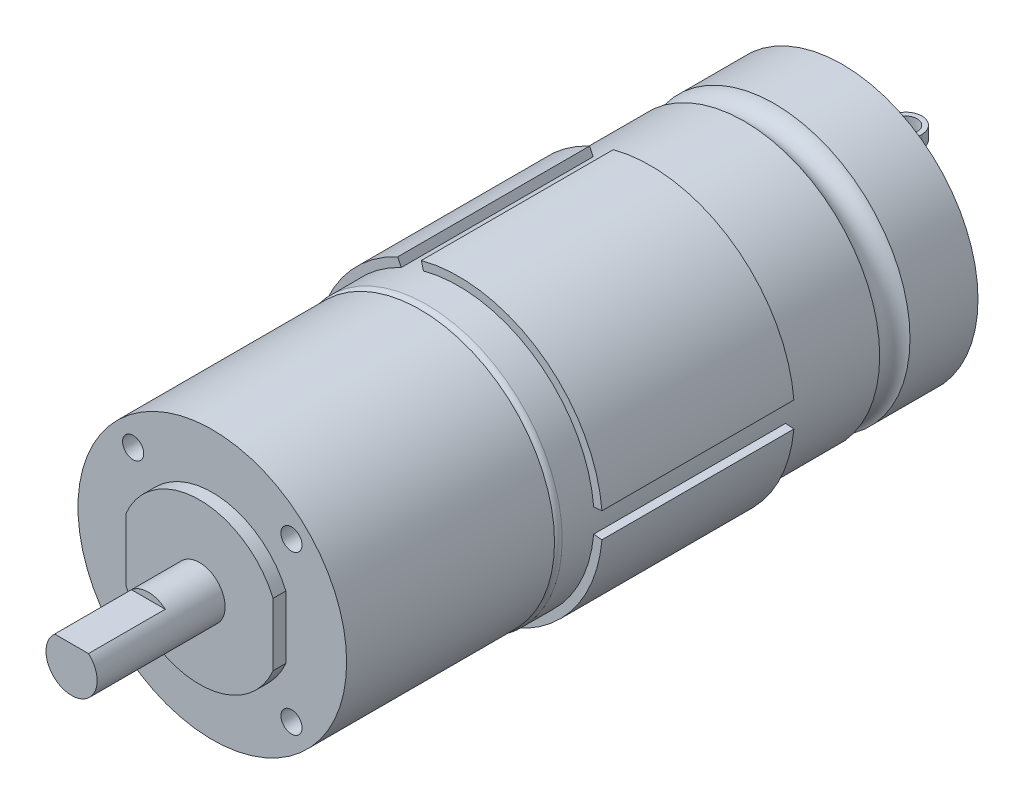
SolidWorks part; units mm, degrees
ref_plane "Piano frontale" through (0, 0, 0) normal (0, 0, 1) x (1, 0, 0)
ref_plane "Piano superiore" through (0, 0, 0) normal (0, 1, 0) x (1, 0, 0)
ref_plane "Piano destro" through (0, 0, 0) normal (1, 0, 0) x (0, 0, -1)
sketch "Schizzo1" plane through (0, 0, 0) normal (0, 0, 1) x (1, 0, 0)
  circle A0 centre (0, 0) radius 21.2
  dimension "D1" = 42.4
extrude "Estrusione-Estrusione1" add sketch "Schizzo1" along normal blind 66
sketch "Schizzo2" plane through (0, 0, 66) normal (0, 0, 1) x (1, 0, 0)
  circle A0 centre (0, 0) radius 21
  dimension "D1" = 42
extrude "Estrusione-Estrusione2" add sketch "Schizzo2" along normal blind 32.5 separate body
sketch "Schizzo3" plane through (0, 0, 98.5) normal (0, 0, 1) x (1, 0, 0)
  circle A0 centre (0, 0) radius 12.5
  dimension "D1" = 25
extrude "Estrusione-Estrusione3" add sketch "Schizzo3" along normal blind 2
sketch "Schizzo4" plane through (0, 0, 100.5) normal (0, 0, 1) x (1, 0, 0)
  line L0 (-12.5, 0) -> (12.5, 0) construction
  line L1 (0, 12.5) -> (0, -12.5) construction
  line L2 (-11.5, 4.899) -> (-11.5, -4.899)
  line L3 (11.5, 4.899) -> (11.5, -4.899)
  circle A1 centre (0, 0) radius 12.5 construction
  arc A4 (11.5, -4.899) -> (11.5, 4.899) centre (0, 0) ccw
  arc A5 (-11.5, 4.899) -> (-11.5, -4.899) centre (0, 0) ccw
  dimension "D1" = 23
  dimension "D2" = 11.5
extrude "Taglio-Estrusione5" cut sketch "Schizzo4" against normal blind 2
sketch "Schizzo5" plane through (0, 0, 100.5) normal (0, 0, 1) x (1, 0, 0)
  circle A0 centre (0, 0) radius 4
  dimension "D1" = 8
extrude "Estrusione-Estrusione4" add sketch "Schizzo5" along normal blind 20
sketch "Schizzo6" plane through (0, 0, 120.5) normal (0, 0, 1) x (1, 0, 0)
  line L0 (-4, 0) -> (4, 0) construction
  line L1 (-2.6458, 3) -> (2.6458, 3)
  circle A1 centre (0, 0) radius 4 construction
  arc A4 (2.6458, 3) -> (-2.6458, 3) centre (0, 0) ccw
  dimension "D1" = 3
extrude "Taglio-Estrusione6" cut sketch "Schizzo6" against normal blind 12
sketch "Schizzo7" plane through (0, 0, 98.5) normal (0, 0, 1) x (1, 0, 0)
  line L2 (0, 0) -> (21, 0) construction
  line L3 (0, 0) -> (14.8492, 14.8492) construction
  circle A1 centre (12.3744, 12.3744) radius 2
  circle A5 centre (0, 0) radius 17.5 construction
  circle A8 centre (12.3744, -12.3744) radius 2
  circle A9 centre (-12.3744, -12.3744) radius 2
  circle A10 centre (-12.3744, 12.3744) radius 2
  point P1 (0, 0)
  point P4 (13.6196, -14.5817)
  point P8 (0, 0)
  point P9 (0, 0)
  dimension "D1" = 4
  dimension "D4" = 35
  dimension "D2" = 45
  dimension "D3" = 4
sketch "Schizzo9" plane through (0, 0, 0) normal (1, 0, 0) x (0, 0, -1)
  line L0 (0, 21.2) -> (-66, 21.2) construction
  line L1 (0, -21.2) -> (0, 21.2) construction
  line L2 (-15.37, 21.2) -> (-10.63, 21.2)
  line L3 (0, 0) -> (-40.6364, 0) construction
  arc A0 (-15.37, 21.2) -> (-10.63, 21.2) centre (-13, 21.9957) ccw
  dimension "D1" = 2.5
  dimension "D2" = 10.63
  dimension "D3" = 4.74
revolve "Taglia-Rivoluzione1" cut sketch "Schizzo9" angle 360 about L3
sketch "Schizzo11" plane through (0, 0, 0) normal (0, 0, -1) x (-1, 0, 0)
  circle A0 centre (0, 0) radius 8.64
  dimension "D1" = 17.28
extrude "Estrusione-Estrusione5" add sketch "Schizzo11" along normal blind 5
sketch "Schizzo12" plane through (0, 0, -5) normal (0, 0, -1) x (-1, 0, 0)
  line L0 (-8.64, 0) -> (8.64, 0) construction
  line L1 (2.5, 6) -> (-2.5, 6)
  line L2 (2.5, 6) -> (2.5, 8)
  line L3 (2.5, 8) -> (-2.5, 8)
  line L4 (-2.5, 6) -> (-2.5, 8)
  line L5 (2.5, 6) -> (-2.5, 8) construction
  line L6 (2.5, 8) -> (-2.5, 6) construction
  line L7 (2.5, -8) -> (-2.5, -8)
  line L8 (2.5, -8) -> (2.5, -6)
  line L9 (2.5, -6) -> (-2.5, -6)
  line L10 (-2.5, -8) -> (-2.5, -6)
  line L11 (2.5, -8) -> (-2.5, -6) construction
  line L12 (2.5, -6) -> (-2.5, -8) construction
  line L13 (0, 8.64) -> (0, -8.64) construction
  circle A0 centre (0, 0) radius 8.64 construction
  circle A1 centre (0, 0) radius 8.64 construction
  point P0 (0, 7)
  point P5 (0, -7)
  point P19 (0, 0)
  point P20 (0, 0)
  dimension "D1" = 5
  dimension "D2" = 5
  dimension "D3" = 2
  dimension "D4" = 2
  dimension "D5" = 8
  dimension "D6" = 8
extrude "Estrusione-Estrusione6" add sketch "Schizzo12" along normal blind 7.42
sketch "Schizzo13" plane through (0, 8, 0) normal (0, 1, 0) x (1, 0, 0)
  line L0 (0, 0) -> (0, 12.42) construction
  line L1 (-2.5, 12.42) -> (2.5, 12.42) construction
  line L2 (-2.5, 5) -> (2.5, 5) construction
  line L3 (-2.5, 12.42) -> (-2.5, 5) construction
  line L4 (2.5, 12.42) -> (2.5, 5) construction
  line L5 (-2.5, 9.92) -> (2.5, 9.92) construction
  line L6 (-2.5, 9.92) -> (-2.5, 12.42)
  line L7 (-2.5, 12.42) -> (2.5, 12.42)
  line L8 (2.5, 12.42) -> (2.5, 9.92)
  circle A0 centre (0, 9.92) radius 1.75
  arc A1 (-2.5, 9.92) -> (2.5, 9.92) centre (0, 9.92) cw
  line M2 (2.5, 5) -> (2.5, 12.42)
  line M3 (2.5, 12.42) -> (-2.5, 12.42)
  line M4 (-2.5, 12.42) -> (-2.5, 5)
  dimension "D1" = 3.5
  dimension "D2" = 4.92
extrude "Taglio-Estrusione4" cut sketch "Schizzo13" against normal blind 16 contours A0 | A1 L7 M4 | A1 M3 M2
fillet "Raccordo2" radius 1 1 edges at (21.2, 0, 66)
hole_wizard "Foro filettato M4-1" positions "Schizzo17" profile "Schizzo18" tap size "M4" standard "ISO"
sketch "Schizzo17" plane through (0, 0, 98.5) normal (0, 0, 1) x (1, 0, 0)
  point P0 (-12.3744, 12.3744)
  point P3 (12.3744, 12.3744)
  point P6 (12.3744, -12.3744)
  point P9 (-12.3744, -12.3744)
sketch "Schizzo18" plane through (-12.3744, 12.3744, 98.5) normal (1, 0, 0) x (0, -1, 0)
  line L0 (0, 0) -> (0, 12.4914)
  line L1 (0, 12.4914) -> (1.65, 11.5)
  line L2 (1.65, 11.5) -> (1.65, 0)
  line L5 (1.65, 0) -> (0, 0)
  line L10 (0, 12.4914) -> (-1.65, 11.5) construction
  line L11 (0, -6.35) -> (0, 107.95) construction
  dimension "Tap Drill Dia." = 3.3
  dimension "Tap Drill Depth" = 11.5
  dimension "Drill Angle" = 118
cosmetic thread "Filettatura del foro1" parameters "D1"=8, "D2"=4
cosmetic thread "Filettatura del foro2" parameters "D1"=8, "D2"=4
cosmetic thread "Filettatura del foro3" parameters "D1"=8, "D2"=4
cosmetic thread "Filettatura del foro4" parameters "D1"=8, "D2"=4
ref_plane "Piano2" through (0, 0, 60) normal (0, 0, -1) x (-1, 0, 0)
sketch "Schizzo19" plane through (0, 0, 60) normal (0, 0, -1) x (-1, 0, 0)
  circle A0 centre (0, 0) radius 22.5
  dimension "D1" = 45
extrude "Estrusione-Estrusione7" add sketch "Schizzo19" along normal blind 30
sketch "Schizzo20" plane through (0, 0, 60) normal (0, 0, -1) x (-1, 0, 0)
  line L0 (0, 0) -> (-22.5, 0) construction
  line L1 (-22.4144, 1.961) -> (-21.1193, 1.8477)
  line L2 (-22.4144, -1.961) -> (-21.1193, -1.8477)
  line L3 (-21.1193, 1.8477) -> (-21.1193, -1.8477) construction
  line L4 (9.5089, 20.3919) -> (8.9595, 19.2137)
  line L5 (5.8234, 21.7333) -> (5.487, 20.4776)
  line L6 (15.9099, -15.9099) -> (14.9907, -14.9907)
  line L7 (18.4309, -12.9055) -> (17.366, -12.1598)
  line L8 (0, 0) -> (-21.1193, 1.8477) construction
  line L9 (0, 0) -> (8.9595, 19.2137) construction
  arc A0 (-22.4144, 1.961) -> (-22.4144, -1.961) centre (0, 0) ccw
  arc A1 (-21.1193, 1.8477) -> (-21.1193, -1.8477) centre (0, 0) ccw
  circle A2 centre (0, 0) radius 22.5 construction
  circle A3 centre (0, 0) radius 21.2 construction
  arc A4 (8.9595, 19.2137) -> (5.487, 20.4776) centre (0, 0) ccw
  arc A5 (9.5089, 20.3919) -> (5.8234, 21.7333) centre (0, 0) ccw
  arc A6 (14.9907, -14.9907) -> (17.366, -12.1598) centre (0, 0) ccw
  arc A7 (15.9099, -15.9099) -> (18.4309, -12.9055) centre (0, 0) ccw
  dimension "D1" = 10
  dimension "D2" = 5
  dimension "D3" = 3
  dimension "D4" = 110
extrude "Taglio-Estrusione9" cut sketch "Schizzo20" along normal blind 30
